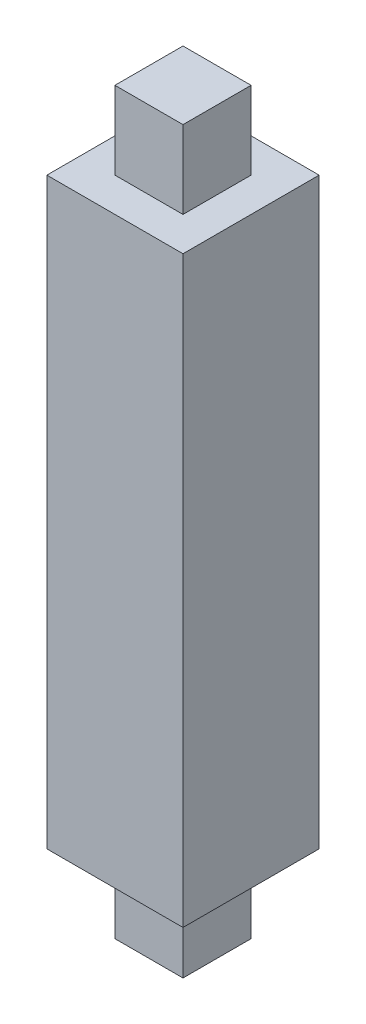
SolidWorks part; units mm, degrees
ref_plane "Front Plane" through (0, 0, 0) normal (0, 0, 1) x (1, 0, 0)
ref_plane "Top Plane" through (0, 0, 0) normal (0, 1, 0) x (1, 0, 0)
ref_plane "Right Plane" through (0, 0, 0) normal (1, 0, 0) x (0, 0, -1)
sketch "Sketch1" plane through (0, 0, 0) normal (0, 1, 0) x (1, 0, 0)
  line L1 (-3.5, 3.5) -> (3.5, 3.5)
  line L2 (-3.5, 3.5) -> (-3.5, -3.5)
  line L3 (-3.5, -3.5) -> (3.5, -3.5)
  line L4 (3.5, 3.5) -> (3.5, -3.5)
  line L5 (-3.5, 3.5) -> (3.5, -3.5) construction
  line L6 (-3.5, -3.5) -> (3.5, 3.5) construction
  point P0 (0, 0)
  dimension "D1" = 7
extrude "Boss-Extrude1" add sketch "Sketch1" along normal mid plane 30
sketch "Sketch2" plane through (0, 15, 0) normal (0, 1, 0) x (1, 0, 0)
  line L1 (-1.75, 1.75) -> (1.75, 1.75)
  line L2 (-1.75, 1.75) -> (-1.75, -1.75)
  line L3 (-1.75, -1.75) -> (1.75, -1.75)
  line L4 (1.75, 1.75) -> (1.75, -1.75)
  line L5 (-1.75, 1.75) -> (1.75, -1.75) construction
  line L6 (-1.75, -1.75) -> (1.75, 1.75) construction
  point P0 (0, 0)
  dimension "D1" = 3.5
extrude "Boss-Extrude2" add sketch "Sketch2" along normal blind 4
sketch "Sketch3" plane through (0, -15, 0) normal (0, -1, 0) x (1, 0, 0)
  line L1 (1.75, -1.75) -> (-1.75, -1.75)
  line L2 (1.75, -1.75) -> (1.75, 1.75)
  line L3 (1.75, 1.75) -> (-1.75, 1.75)
  line L4 (-1.75, -1.75) -> (-1.75, 1.75)
  line L5 (1.75, -1.75) -> (-1.75, 1.75) construction
  line L6 (1.75, 1.75) -> (-1.75, -1.75) construction
  point P0 (0, 0)
  dimension "D1" = 3.5
extrude "Boss-Extrude3" add sketch "Sketch3" along normal blind 4
